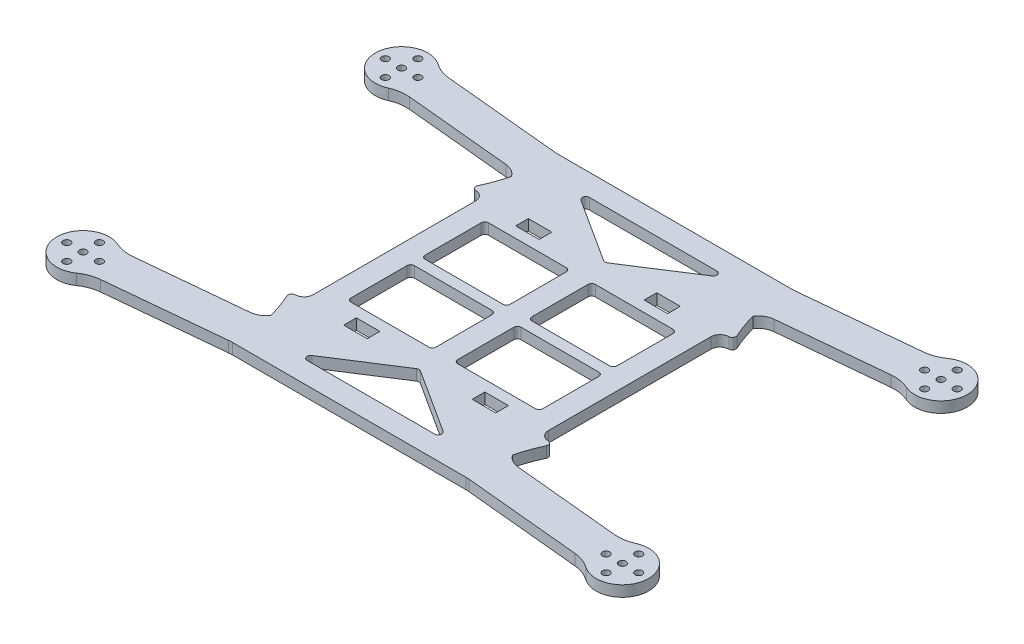
SolidWorks part; units mm, degrees
material "PLA"
ref_plane "Front Plane" through (0, 0, 0) normal (0, 0, 1) x (1, 0, 0)
ref_plane "Top Plane" through (0, 0, 0) normal (0, 1, 0) x (1, 0, 0)
ref_plane "Right Plane" through (0, 0, 0) normal (1, 0, 0) x (0, 0, -1)
sketch "Sketch1" plane through (0, 0, 0) normal (0, 1, 0) x (1, 0, 0)
  line L0 (-65.5414, 48.1601) -> (-33.2187, 45.0461)
  line L1 (-32.2597, -45) -> (32.2597, -45)
  line L2 (-32.5, -22.4419) -> (-32.5, 22.4419)
  line L3 (-32.2597, 45) -> (32.2597, 45)
  line L4 (32.5, -22.4419) -> (32.5, 22.4419)
  line L5 (0, 45) -> (0, -45) construction
  line L6 (-32.5, 0) -> (32.5, 0) construction
  line L7 (-66.5004, 38.2062) -> (-37.0205, 35.3661)
  line L8 (-74.5, 44) -> (-32.5933, 39.9627) construction
  line L9 (-74.5, -44) -> (-32.5933, -39.9627) construction
  line L10 (0, -55) -> (0, 55) construction
  line L11 (-66.5004, -38.2062) -> (-37.0205, -35.3661)
  line L12 (-65.5414, -48.1601) -> (-33.2187, -45.0461)
  line L13 (74.5, -44) -> (32.5933, -39.9627) construction
  line L14 (65.5414, -48.1601) -> (33.2187, -45.0461)
  line L15 (66.5004, -38.2062) -> (37.0205, -35.3661)
  line L16 (74.5, 44) -> (32.5933, 39.9627) construction
  line L17 (66.5004, 38.2062) -> (37.0205, 35.3661)
  line L18 (65.5414, 48.1601) -> (33.2187, 45.0461)
  arc A34 (-70.3318, 49.932) -> (-71.5409, 37.3814) centre (-74.5, 44) ccw
  circle A35 centre (-74.5, 44) radius 4.5 construction
  circle A36 centre (-79, 44) radius 1
  circle A49 centre (79, -44) radius 1
  circle A55 centre (79, 44) radius 1
  arc A58 (-33.3868, 33.2319) -> (-37.0205, 35.3661) centre (-37.5, 30.3891) ccw
  arc A59 (-32.2597, 45) -> (-33.2187, 45.0461) centre (-32.2597, 55) cw
  circle A60 centre (-74.5, 48.5) radius 1
  circle A61 centre (-70, 44) radius 1
  circle A62 centre (-74.5, 39.5) radius 1
  arc A63 (-66.5004, 38.2062) -> (-71.5409, 37.3814) centre (-67.4593, 28.2522) ccw
  arc A64 (-70.3318, 49.932) -> (-65.5414, 48.1601) centre (-64.5824, 58.114) ccw
  arc A65 (-33.3868, -33.2319) -> (-37.0205, -35.3661) centre (-37.5, -30.3891) cw
  circle A66 centre (-74.5, -44) radius 4.5 construction
  arc A67 (-70.3318, -49.932) -> (-65.5414, -48.1601) centre (-64.5824, -58.114) cw
  arc A68 (-66.5004, -38.2062) -> (-71.5409, -37.3814) centre (-67.4593, -28.2522) cw
  circle A69 centre (-74.5, -39.5) radius 1
  circle A70 centre (-70, -44) radius 1
  circle A71 centre (-74.5, -48.5) radius 1
  arc A72 (-32.2597, -45) -> (-33.2187, -45.0461) centre (-32.2597, -55) ccw
  circle A73 centre (-79, -44) radius 1
  arc A74 (-70.3318, -49.932) -> (-71.5409, -37.3814) centre (-74.5, -44) cw
  circle A75 centre (74.5, -44) radius 4.5 construction
  arc A76 (70.3318, -49.932) -> (71.5409, -37.3814) centre (74.5, -44) ccw
  circle A77 centre (79, -44) radius 1
  arc A78 (32.2597, -45) -> (33.2187, -45.0461) centre (32.2597, -55) cw
  circle A79 centre (74.5, -48.5) radius 1
  circle A80 centre (70, -44) radius 1
  circle A81 centre (74.5, -39.5) radius 1
  arc A82 (66.5004, -38.2062) -> (71.5409, -37.3814) centre (67.4593, -28.2522) ccw
  arc A83 (70.3318, -49.932) -> (65.5414, -48.1601) centre (64.5824, -58.114) ccw
  arc A84 (33.3868, -33.2319) -> (37.0205, -35.3661) centre (37.5, -30.3891) ccw
  circle A85 centre (74.5, 44) radius 4.5 construction
  arc A86 (70.3318, 49.932) -> (65.5414, 48.1601) centre (64.5824, 58.114) cw
  arc A87 (66.5004, 38.2062) -> (71.5409, 37.3814) centre (67.4593, 28.2522) cw
  circle A88 centre (74.5, 39.5) radius 1
  circle A89 centre (70, 44) radius 1
  circle A90 centre (74.5, 48.5) radius 1
  arc A91 (32.2597, 45) -> (33.2187, 45.0461) centre (32.2597, 55) ccw
  arc A92 (33.3868, 33.2319) -> (37.0205, 35.3661) centre (37.5, 30.3891) cw
  circle A93 centre (79, 44) radius 1
  arc A94 (70.3318, 49.932) -> (71.5409, 37.3814) centre (74.5, 44) cw
  circle A95 centre (-74.5, -44) radius 1
  circle A96 centre (-74.5, 44) radius 1
  circle A97 centre (74.5, 44) radius 1
  circle A98 centre (74.5, -44) radius 1
  arc A99 (-35.8354, 26.3563) -> (-33.3868, 33.2319) centre (-74.5, 44) ccw
  arc A100 (-32.5, 22.4419) -> (-34.9469, 24.9414) centre (-35, 22.4419) ccw
  arc A101 (-35.8354, 26.3563) -> (-34.9469, 24.9414) centre (-34.9257, 25.9411) ccw
  arc A102 (35.8354, 26.3563) -> (33.3868, 33.2319) centre (74.5, 44) cw
  arc A103 (32.5, 22.4419) -> (34.9469, 24.9414) centre (35, 22.4419) cw
  arc A104 (35.8354, 26.3563) -> (34.9469, 24.9414) centre (34.9257, 25.9411) cw
  arc A105 (35.8354, -26.3563) -> (33.3868, -33.2319) centre (74.5, -44) ccw
  arc A106 (35.8354, -26.3563) -> (34.9469, -24.9414) centre (34.9257, -25.9411) ccw
  arc A107 (32.5, -22.4419) -> (34.9469, -24.9414) centre (35, -22.4419) ccw
  arc A108 (-35.8354, -26.3563) -> (-34.9469, -24.9414) centre (-34.9257, -25.9411) cw
  arc A109 (-32.5, -22.4419) -> (-34.9469, -24.9414) centre (-35, -22.4419) cw
  arc A110 (-35.8354, -26.3563) -> (-33.3868, -33.2319) centre (-74.5, -44) cw
  point P0 (0, 0)
  point P23 (-32.7403, 45)
  point P28 (-70, 70)
  point P40 (-74.5, 44)
  point P66 (-74.5, -44)
  point P68 (-70, -70)
  point P69 (-32.7403, -45)
  point P90 (32.7403, -45)
  point P91 (74.5, -44)
  point P113 (74.5, 44)
  point P114 (70, 70)
  point P115 (32.7403, 45)
  dimension "D3" = 44
  dimension "D5" = 45
  dimension "D8" = 14.5
  dimension "D9" = 10
  dimension "D10" = 2
  dimension "D4" = 64.5194
  dimension "D7" = 32.5
  dimension "D6" = 6.364
  dimension "D11" = 9
  dimension "D12" = 2
  dimension "D13" = 10
  dimension "D14" = 85
  dimension "D15" = 5
  dimension "D18" = 10
  dimension "D20" = 10
  dimension "D21" = 10
  dimension "D22" = 2
  dimension "D16" = 65
  dimension "D17" = 5
  dimension "D19" = 4
extrude "Boss-Extrude1" add sketch "Sketch1" along normal blind 3 contours A94 A86 L18 A91 L3 A59 L0 A64 A34 A63 L7 A58 L2 A65 L11 A68 A74 A67 L12 A72 L1 A78 L14 A83 A76 A82 L15 A84 L4 A92 L17 A87 A89 A73 A70 A55 A36 A49 A60 A61 A62
sketch "Sketch2" plane through (0, 3, 0) normal (0, 1, 0) x (1, 0, 0)
  line L0 (-1.65, 0) -> (1.65, 0) construction
  line L1 (-21, 25.5) -> (-14.5, 25.5)
  line L2 (-21, 25.5) -> (-21, 22)
  line L3 (-21, 22) -> (-14.5, 22)
  line L4 (-14.5, 25.5) -> (-14.5, 22)
  line L5 (-14.5, -25.5) -> (-14.5, -22)
  line L6 (-21, -22) -> (-14.5, -22)
  line L7 (-21, -25.5) -> (-21, -22)
  line L8 (-21, -25.5) -> (-14.5, -25.5)
  line L9 (0, -1.65) -> (0, 1.65) construction
  line L10 (21, -25.5) -> (14.5, -25.5)
  line L11 (21, -25.5) -> (21, -22)
  line L12 (21, -22) -> (14.5, -22)
  line L13 (14.5, -25.5) -> (14.5, -22)
  line L14 (14.5, 25.5) -> (14.5, 22)
  line L15 (21, 22) -> (14.5, 22)
  line L16 (21, 25.5) -> (21, 22)
  line L17 (21, 25.5) -> (14.5, 25.5)
  line L18 (-25.5, 19) -> (-4, 19)
  line L19 (-25.5, -1.5) -> (-4, -1.5)
  line L20 (-26.5, -2.5) -> (-26.5, -18)
  line L21 (-25.5, -19) -> (-4, -19)
  line L22 (-3, -2.5) -> (-3, -18)
  line L23 (-26.5, 18) -> (-26.5, 2.5)
  line L24 (-25.5, 1.5) -> (-4, 1.5)
  line L25 (-3, 18) -> (-3, 2.5)
  line L26 (4, 19) -> (25.5, 19)
  line L27 (3, 18) -> (3, 2.5)
  line L28 (4, 1.5) -> (25.5, 1.5)
  line L29 (26.5, 18) -> (26.5, 2.5)
  line L30 (4, -1.5) -> (25.5, -1.5)
  line L31 (3, -2.5) -> (3, -18)
  line L32 (4, -19) -> (25.5, -19)
  line L33 (26.5, -2.5) -> (26.5, -18)
  line L34 (-32.5, -22.4419) -> (-32.5, 22.4419) construction
  line L35 (32.5, -22.4419) -> (32.5, 22.4419) construction
  line L36 (-17.5952, 39) -> (17.5952, 39)
  line L37 (18.1359, 37.1588) -> (0.5408, 25.8476)
  line L38 (-0.5408, 25.8476) -> (-18.1359, 37.1588)
  line L39 (-32.2597, 45) -> (32.2597, 45) construction
  line L40 (-17.5952, -39) -> (17.5952, -39)
  line L41 (18.1359, -37.1588) -> (0.5408, -25.8476)
  line L42 (-0.5408, -25.8476) -> (-18.1359, -37.1588)
  line L43 (-32.2597, -45) -> (32.2597, -45) construction
  arc A0 (0.5408, -25.8476) -> (-0.5408, -25.8476) centre (0, -26.6888) ccw
  arc A1 (17.5952, -39) -> (18.1359, -37.1588) centre (17.5952, -38) ccw
  arc A2 (-17.5952, -39) -> (-18.1359, -37.1588) centre (-17.5952, -38) cw
  arc A3 (26.5, -18) -> (25.5, -19) centre (25.5, -18) cw
  arc A4 (26.5, -2.5) -> (25.5, -1.5) centre (25.5, -2.5) ccw
  arc A5 (3, -2.5) -> (4, -1.5) centre (4, -2.5) cw
  arc A6 (3, -18) -> (4, -19) centre (4, -18) ccw
  arc A7 (-25.5, -19) -> (-26.5, -18) centre (-25.5, -18) cw
  arc A8 (-3, -18) -> (-4, -19) centre (-4, -18) cw
  arc A9 (-3, -2.5) -> (-4, -1.5) centre (-4, -2.5) ccw
  arc A10 (-25.5, -1.5) -> (-26.5, -2.5) centre (-25.5, -2.5) ccw
  arc A11 (-25.5, 1.5) -> (-26.5, 2.5) centre (-25.5, 2.5) cw
  arc A12 (-3, 18) -> (-4, 19) centre (-4, 18) ccw
  arc A13 (-26.5, 18) -> (-25.5, 19) centre (-25.5, 18) cw
  arc A14 (-3, 2.5) -> (-4, 1.5) centre (-4, 2.5) cw
  arc A15 (3, 2.5) -> (4, 1.5) centre (4, 2.5) ccw
  arc A16 (26.5, 2.5) -> (25.5, 1.5) centre (25.5, 2.5) cw
  arc A17 (26.5, 18) -> (25.5, 19) centre (25.5, 18) ccw
  arc A18 (4, 19) -> (3, 18) centre (4, 18) ccw
  arc A19 (18.1359, 37.1588) -> (17.5952, 39) centre (17.5952, 38) ccw
  arc A20 (-17.5952, 39) -> (-18.1359, 37.1588) centre (-17.5952, 38) ccw
  arc A21 (0.5408, 25.8476) -> (-0.5408, 25.8476) centre (0, 26.6888) cw
  point P53 (0, -25.5)
  point P56 (21, -39)
  point P59 (-21, -39)
  point P68 (3, -19)
  point P73 (-3, -19)
  point P96 (21, 39)
  point P99 (-21, 39)
  point P102 (0, 25.5)
  dimension "D21" = 1
  dimension "D1" = 3.5
  dimension "D2" = 6.5
  dimension "D3" = 14.5
  dimension "D4" = 22
  dimension "D5" = 6
  dimension "D6" = 6
  dimension "D7" = 6
  dimension "D8" = 3
  dimension "D9" = 3
  dimension "D10" = 3
  dimension "D11" = 3
  dimension "D12" = 6
  dimension "D13" = 3
  dimension "D14" = 3
  dimension "D15" = 6
  dimension "D16" = 6
  dimension "D17" = 3
  dimension "D18" = 1.5
  dimension "D19" = 1.5
  dimension "D20" = 6
  dimension "D23" = 42
  dimension "D24" = 6
extrude "Cut-Extrude1" cut sketch "Sketch2" against normal blind 3
